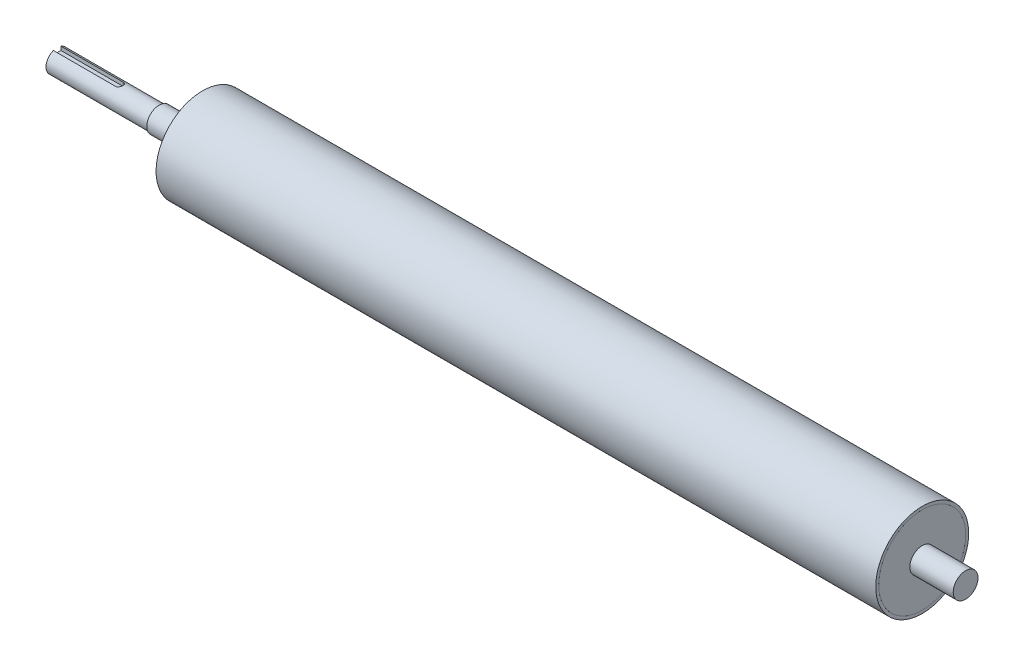
SolidWorks part; units mm, degrees
material "AISI 304"
ref_plane "Front Plane" through (0, 0, 0) normal (0, 0, 1) x (1, 0, 0)
ref_plane "Top Plane" through (0, 0, 0) normal (0, 1, 0) x (1, 0, 0)
ref_plane "Right Plane" through (0, 0, 0) normal (1, 0, 0) x (0, 0, -1)
sketch "Sketch1" plane through (0, 0, 0) normal (0, 0, 1) x (1, 0, 0)
  line L0 (-290.3, 37.5) -> (290.3, 37.5)
  line L1 (290.3, 37.5) -> (290.3, 35.1005)
  line L2 (290.3, 35.1005) -> (-290.3, 35.1005)
  line L3 (-290.3, 35.1005) -> (-290.3, 37.5)
  line L4 (-290.3, 0) -> (290.3, 0) construction
  point P8 (0, 0)
  dimension "D1" = 580.6
  dimension "D2" = 75
  dimension "D3" = 70.201
revolve "Revolve1" add sketch "Sketch1" angle 360 about L4
sketch "Sketch2" plane through (-290.3, 0, 0) normal (-1, 0, 0) x (0, 0, 1)
  circle A1 centre (0, 0) radius 35.1
  circle A2 centre (0, 0) radius 10.0005
  dimension "D1" = 20.001
  dimension "D2" = 70.2
extrude "Boss-Extrude1" add sketch "Sketch2" against normal blind 10
sketch "Sketch3" plane through (290.3, 0, 0) normal (1, 0, 0) x (0, 0, -1)
  circle A0 centre (0, 0) radius 10.0005 construction
  circle A1 centre (0, 0) radius 35.1
  circle A2 centre (0, 0) radius 35.1
  circle A3 centre (0, 0) radius 10.0005
  dimension "D1" = 0
extrude "Boss-Extrude2" add sketch "Sketch3" against normal blind 10 separate body
sketch "Sketch4" plane through (0, 0, 0) normal (0, 0, 1) x (1, 0, 0)
  line L0 (-325.3, 10) -> (325.3, 10)
  line L1 (-290.3, 10.0005) -> (-290.3, -10.0005) construction
  line L6 (325.3, 0) -> (-407.6, 0) construction
  line L8 (-290.3, 10.0005) -> (-290.3, -10.0005) construction
  line L9 (-325.3, 10) -> (-325.3, 9)
  line L10 (-407.6, 0) -> (325.3, 0) construction
  line L11 (-407.6, 0) -> (325.3, 0)
  line L14 (325.3, 10) -> (325.3, 0)
  line L15 (-325.3, 9) -> (-407.6, 9)
  line L16 (-407.6, 9) -> (-407.6, 0)
  line L17 (-290.3, 35.1) -> (-290.3, -35.1) construction
  line L18 (290.3, -35.1) -> (290.3, 35.1) construction
  point P17 (325.3, 5)
  dimension "D1" = 18
  dimension "D2" = 35
  dimension "D3" = 82.3
  dimension "D5" = 35
  dimension "D7" = 20
revolve "Revolve3" add sketch "Sketch4" angle 360 about L11
ref_plane "Plane1" through (0, 9, 0) normal (0, 1, 0) x (1, 0, 0)
sketch "Sketch5" plane through (0, 9, 0) normal (0, 1, 0) x (1, 0, 0)
  line L0 (-407.6, 3) -> (-357.6, 3)
  line L1 (-407.6, 9) -> (-407.6, -9) construction
  line L2 (-357.6, -3) -> (-407.6, -3)
  line L3 (-407.6, -3) -> (-407.6, 3)
  line L4 (-407.6, 9) -> (-407.6, -9) construction
  arc A0 (-357.6, 3) -> (-357.6, -3) centre (-357.6, 0) cw
  point P6 (-407.6, 0)
  point P8 (-407.6, 0)
  dimension "D1" = 6
  dimension "D2" = 50
extrude "Cut-Extrude1" cut sketch "Sketch5" against normal blind 3.5
